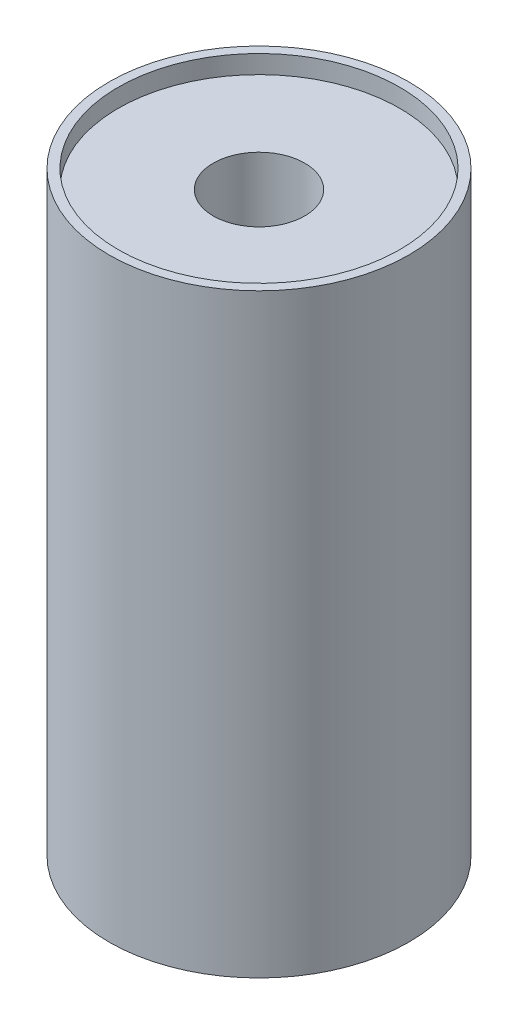
SolidWorks part; units mm, degrees
material "HYPALON"
ref_plane "Front Plane" through (0, 0, 0) normal (0, 0, 1) x (1, 0, 0)
ref_plane "Top Plane" through (0, 0, 0) normal (0, 1, 0) x (1, 0, 0)
ref_plane "Right Plane" through (0, 0, 0) normal (1, 0, 0) x (0, 0, -1)
sketch "Sketch1" plane through (0, 0, 0) normal (0, 1, 0) x (1, 0, 0)
  circle A1 centre (0, 0) radius 41.5925
  dimension "D1" = 83.185
extrude "Boss-Extrude1" add sketch "Sketch1" along normal blind 165.1
sketch "Sketch2" plane through (0, 165.1, 0) normal (0, 1, 0) x (1, 0, 0)
  circle A0 centre (0, 0) radius 12.7
extrude "Cut-Extrude1" cut sketch "Sketch2" against normal through all both and the other way through all
sketch "Sketch3" plane through (0, 165.1, 0) normal (0, 1, 0) x (1, 0, 0)
  circle A0 centre (0, 0) radius 39.0525
  circle A1 centre (0, 0) radius 41.5925 construction
  dimension "D1" = 2.54
extrude "Cut-Extrude2" cut sketch "Sketch3" against normal blind 5.08
sketch "Sketch4" plane through (0, 0, 0) normal (0, -1, 0) x (1, 0, 0)
  circle A0 centre (0, 0) radius 41.5925 construction
  circle A1 centre (0, 0) radius 41.5925
  circle A2 centre (0, 0) radius 39.0525
  circle M3 centre (0, 0) radius 12.7
  dimension "D1" = 2.54
extrude "Cut-Extrude3" cut sketch "Sketch4" against normal blind 2.54 contours A2 M3
